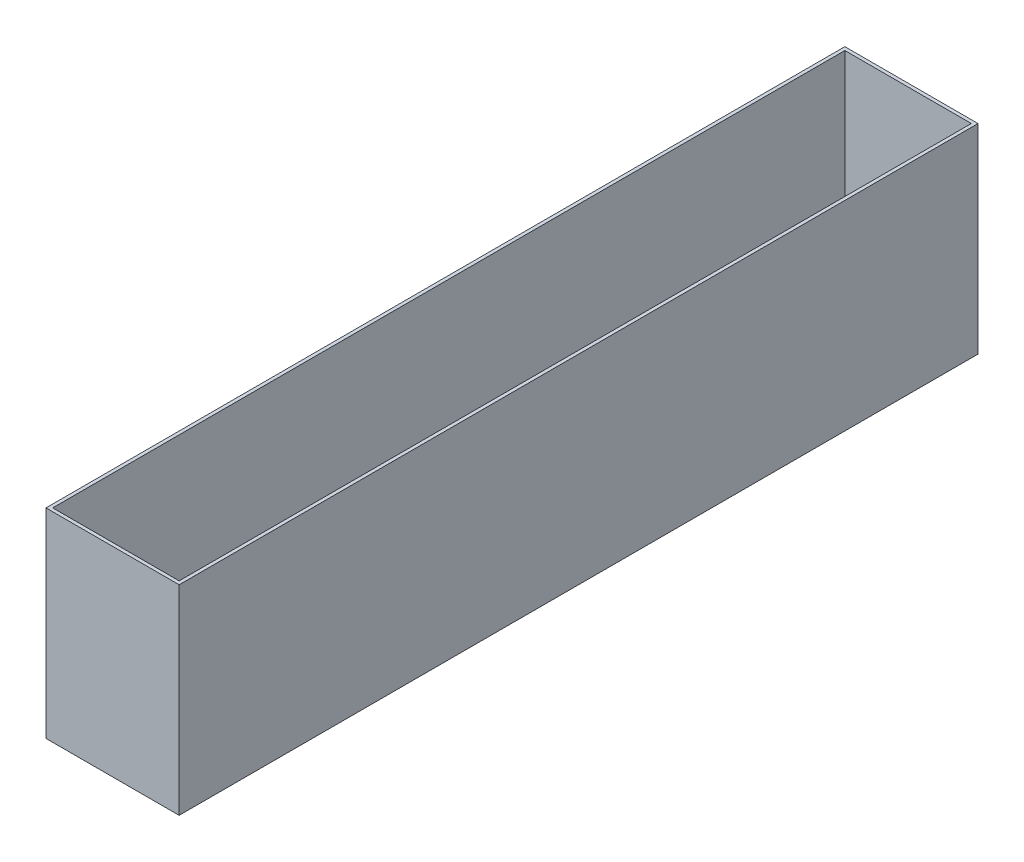
SolidWorks part; units mm, degrees
material "Acrylic (Medium-high impact)"
ref_plane "Front Plane" through (0, 0, 0) normal (0, 0, 1) x (1, 0, 0)
ref_plane "Top Plane" through (0, 0, 0) normal (0, 1, 0) x (1, 0, 0)
ref_plane "Right Plane" through (0, 0, 0) normal (1, 0, 0) x (0, 0, -1)
sketch "Sketch1" plane through (0, 0, 0) normal (0, 1, 0) x (1, 0, 0)
  line L1 (0, 0) -> (200, 0)
  line L2 (0, 0) -> (0, -1200)
  line L3 (0, -1200) -> (200, -1200)
  line L4 (200, 0) -> (200, -1200)
  dimension "D1" = 200
  dimension "D2" = 1200
extrude "Boss-Extrude1" add sketch "Sketch1" along normal blind 300
sketch "Sketch2" plane through (0, 300, 0) normal (0, 1, 0) x (1, 0, 0)
  line L0 (200, 0) -> (0, 0) construction
  line L1 (5, -5) -> (195, -5)
  line L2 (5, -5) -> (5, -1195)
  line L3 (5, -1195) -> (195, -1195)
  line L4 (195, -5) -> (195, -1195)
  line L5 (0, 0) -> (0, -1200) construction
  dimension "D1" = 190
  dimension "D2" = 1190
  dimension "D3" = 5
  dimension "D4" = 5
extrude "Cut-Extrude1" cut sketch "Sketch2" against normal blind 290
